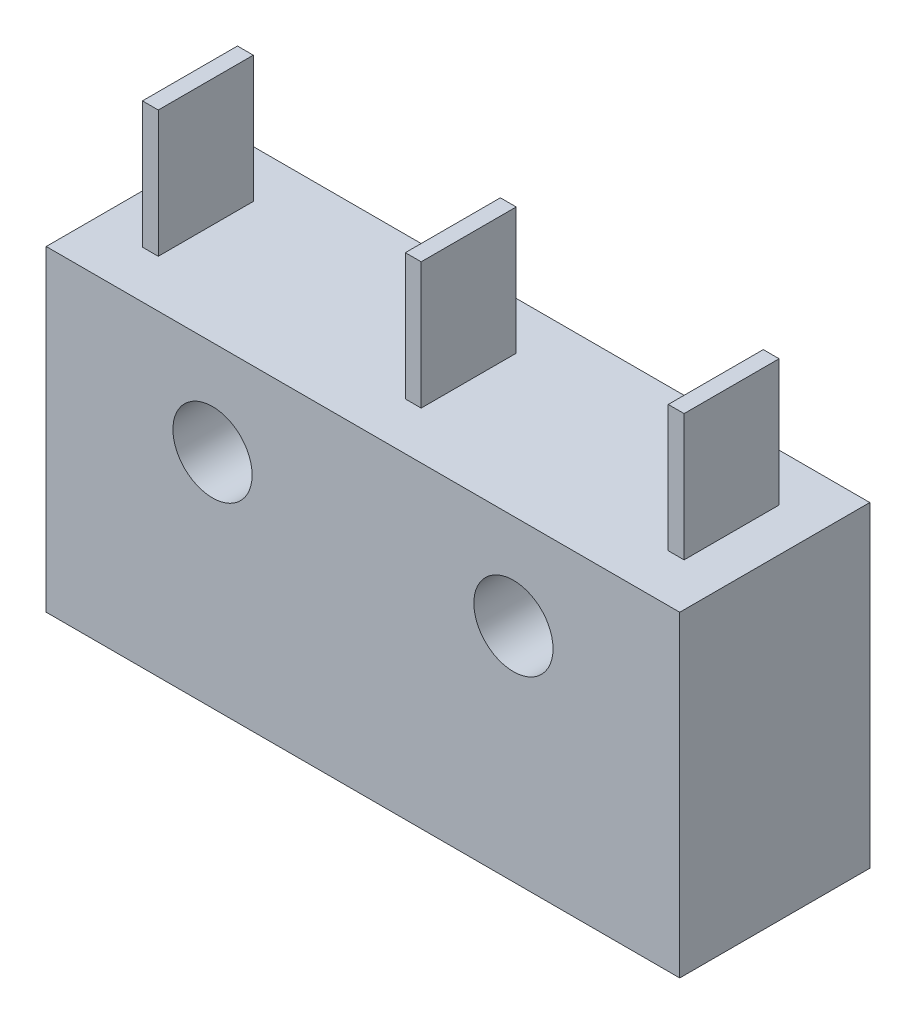
SolidWorks part; units mm, degrees
ref_plane "Front Plane" through (0, 0, 0) normal (0, 0, 1) x (1, 0, 0)
ref_plane "Top Plane" through (0, 0, 0) normal (0, 1, 0) x (1, 0, 0)
ref_plane "Right Plane" through (0, 0, 0) normal (1, 0, 0) x (0, 0, -1)
sketch "Sketch1" plane through (0, 0, 0) normal (0, 0, 1) x (1, 0, 0)
  line L1 (-10, 5) -> (10, 5)
  line L2 (-10, 5) -> (-10, -5)
  line L3 (-10, -5) -> (10, -5)
  line L4 (10, 5) -> (10, -5)
  line L5 (-10, 5) -> (10, -5) construction
  line L6 (-10, -5) -> (10, 5) construction
  point P0 (0, 0)
  dimension "D1" = 20
  dimension "D2" = 10
extrude "Boss-Extrude1" add sketch "Sketch1" along normal blind 6
sketch "Sketch2" plane through (0, 5, 0) normal (0, 1, 0) x (1, 0, 0)
  line L0 (-10, -6) -> (-10, 0) construction
  line L1 (-8.4625, -1.5) -> (-7.9625, -1.5)
  line L2 (-8.4625, -1.5) -> (-8.4625, -4.5)
  line L3 (-8.4625, -4.5) -> (-7.9625, -4.5)
  line L4 (-7.9625, -1.5) -> (-7.9625, -4.5)
  line L5 (-8.4625, -1.5) -> (-7.9625, -4.5) construction
  line L6 (-8.4625, -4.5) -> (-7.9625, -1.5) construction
  line L7 (-0.1625, -1.5) -> (0.3375, -1.5)
  line L8 (-0.1625, -1.5) -> (-0.1625, -4.5)
  line L9 (-0.1625, -4.5) -> (0.3375, -4.5)
  line L10 (0.3375, -1.5) -> (0.3375, -4.5)
  line L11 (8.1375, -1.5) -> (8.6375, -1.5)
  line L12 (8.1375, -1.5) -> (8.1375, -4.5)
  line L13 (8.1375, -4.5) -> (8.6375, -4.5)
  line L14 (8.6375, -1.5) -> (8.6375, -4.5)
  point P0 (-8.2125, -3)
  point P7 (-10, -3)
  dimension "D1" = 3
  dimension "D2" = 0.5
  dimension "D3" = 3
extrude "Boss-Extrude2" add sketch "Sketch2" along normal blind 4
sketch "Sketch3" plane through (0, 0, 6) normal (0, 0, 1) x (1, 0, 0)
  line L0 (10, 5) -> (-10, 5) construction
  line L1 (-4.75, 2) -> (4.75, 2) construction
  line L2 (-10, -5) -> (10, -5) construction
  circle A0 centre (-4.75, 2) radius 1.25
  circle A1 centre (4.75, 2) radius 1.25
  point P6 (0, 2)
  point P9 (0, -5)
  dimension "D1" = 2.5
  dimension "D2" = 3
  dimension "D3" = 9.5
extrude "Cut-Extrude1" cut sketch "Sketch3" against normal through all
